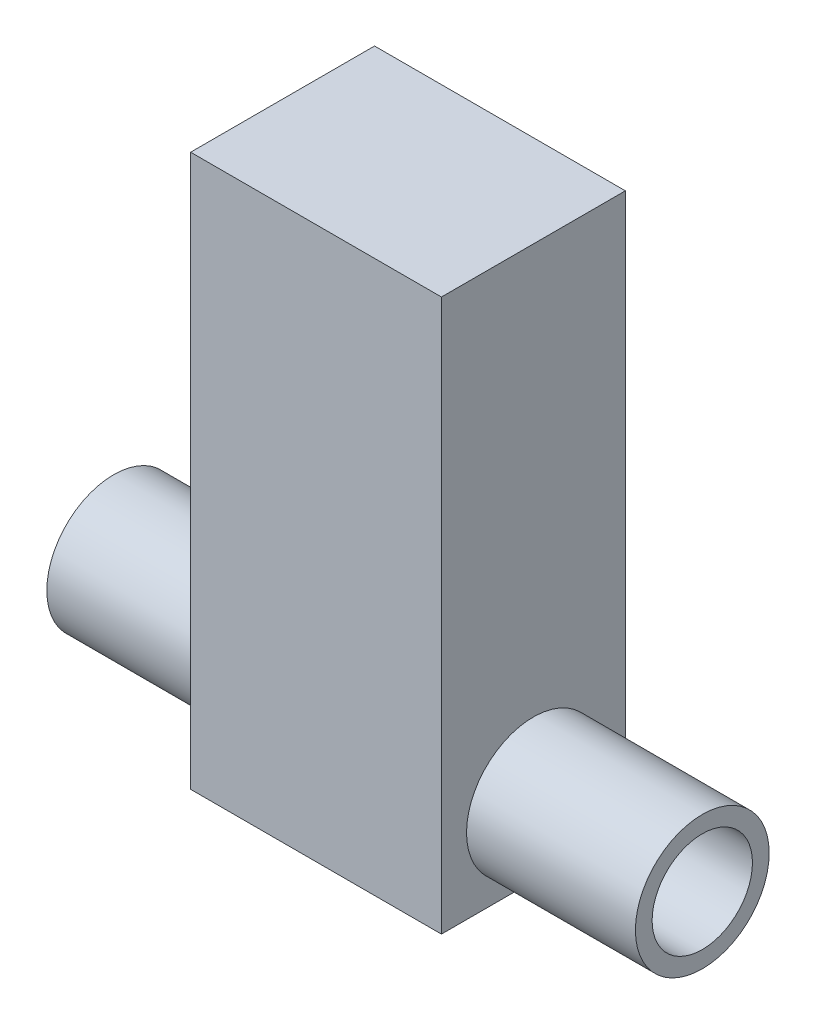
SolidWorks part; units mm, degrees
ref_plane "Front Plane" through (0, 0, 0) normal (0, 0, 1) x (1, 0, 0)
ref_plane "Top Plane" through (0, 0, 0) normal (0, 1, 0) x (1, 0, 0)
ref_plane "Right Plane" through (0, 0, 0) normal (1, 0, 0) x (0, 0, -1)
sketch "Sketch1" plane through (0, 0, 0) normal (0, 1, 0) x (1, 0, 0)
  line L1 (-15, -11) -> (15, -11)
  line L2 (-15, -11) -> (-15, 11)
  line L3 (-15, 11) -> (15, 11)
  line L4 (15, -11) -> (15, 11)
  line L5 (-15, -11) -> (15, 11) construction
  line L6 (-15, 11) -> (15, -11) construction
  point P0 (0, 0)
  dimension "D1" = 22
  dimension "D2" = 30
extrude "Boss-Extrude1" add sketch "Sketch1" along normal blind 66
sketch "Sketch2" plane through (-15, 0, 0) normal (-1, 0, 0) x (0, 0, 1)
  line L0 (-11, 0) -> (11, 0) construction
  circle A0 centre (0, 9) radius 8
  dimension "D1" = 16
  dimension "D2" = 9
extrude "Boss-Extrude2" add sketch "Sketch2" along normal blind 20.2 contours A0
sketch "Sketch3" plane through (15, 0, 0) normal (1, 0, 0) x (0, 0, -1)
  line L0 (-11, 0) -> (11, 0) construction
  circle A0 centre (0, 9) radius 8
  dimension "D1" = 16
  dimension "D2" = 9
extrude "Boss-Extrude3" add sketch "Sketch3" along normal blind 20.2
shell "Shell1" thickness 2
